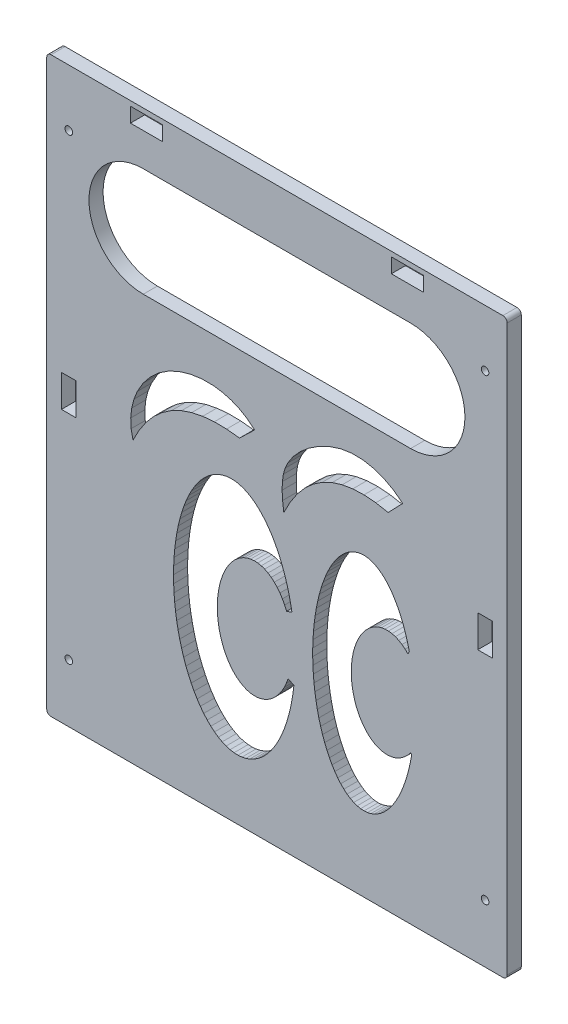
SolidWorks part; units mm, degrees
ref_plane "Front Plane" through (0, 0, 0) normal (0, 0, 1) x (1, 0, 0)
ref_plane "Top Plane" through (0, 0, 0) normal (0, 1, 0) x (1, 0, 0)
ref_plane "Right Plane" through (0, 0, 0) normal (1, 0, 0) x (0, 0, -1)
sketch "Model" plane through (0, 0, 0) normal (0, 0, 1) x (1, 0, 0)
  line L0 (166.4528, 168.5051) -> (162.3208, 171.6508)
  line L1 (162.3208, 171.6508) -> (157.7819, 174.1382)
  line L2 (157.7819, 174.1382) -> (152.9264, 175.8982)
  line L3 (152.9264, 175.8982) -> (147.8445, 176.8622)
  line L4 (147.8445, 176.8622) -> (142.6264, 176.9611)
  line L5 (142.6264, 176.9611) -> (137.3649, 176.1352)
  line L6 (137.3649, 176.1352) -> (132.1849, 174.4433)
  line L7 (132.1849, 174.4433) -> (127.2343, 172.0278)
  line L8 (127.2343, 172.0278) -> (122.6612, 169.0328)
  line L9 (122.6612, 169.0328) -> (118.6141, 165.6027)
  line L10 (118.6141, 165.6027) -> (115.2411, 161.8816)
  line L11 (115.2411, 161.8816) -> (112.6877, 158.0066)
  line L12 (112.6877, 158.0066) -> (111.4758, 155.3153)
  line L13 (111.4758, 155.3153) -> (110.6436, 152.4305)
  line L14 (110.6436, 152.4305) -> (110.1777, 149.2546)
  line L15 (110.1777, 149.2546) -> (110.065, 145.6897)
  line L16 (110.065, 145.6897) -> (110.292, 141.6382)
  line L17 (110.292, 141.6382) -> (110.8456, 137.0023)
  line L18 (110.8456, 137.0023) -> (113.7945, 142.6541)
  line L19 (113.7945, 142.6541) -> (117.0741, 147.6123)
  line L20 (117.0741, 147.6123) -> (120.6843, 151.8768)
  line L21 (120.6843, 151.8768) -> (124.6252, 155.4477)
  line L22 (124.6252, 155.4477) -> (128.8968, 158.3248)
  line L23 (128.8968, 158.3248) -> (133.499, 160.5083)
  line L24 (133.499, 160.5083) -> (138.1411, 161.9316)
  line L25 (138.1411, 161.9316) -> (143.0771, 162.7383)
  line L26 (143.0771, 162.7383) -> (148.3071, 162.9283)
  line L27 (148.3071, 162.9283) -> (153.8311, 162.5017)
  line L28 (153.8311, 162.5017) -> (159.649, 161.4583)
  line L29 (112.8319, 70.6815) -> (112.0081, 68.4661)
  line L30 (112.0081, 68.4661) -> (111.0551, 66.3808)
  line L31 (111.0551, 66.3808) -> (109.9812, 64.4439)
  line L32 (109.9812, 64.4439) -> (108.7959, 62.6723)
  line L33 (108.7959, 62.6723) -> (107.5095, 61.0816)
  line L34 (107.5095, 61.0816) -> (106.1333, 59.6858)
  line L35 (106.1333, 59.6858) -> (104.6795, 58.4971)
  line L36 (104.6795, 58.4971) -> (103.1608, 57.526)
  line L37 (103.1608, 57.526) -> (101.5905, 56.7809)
  line L38 (101.5905, 56.7809) -> (99.9824, 56.2686)
  line L39 (99.9824, 56.2686) -> (98.3507, 55.9933)
  line L40 (98.3507, 55.9933) -> (96.7096, 55.9576)
  line L41 (96.7096, 55.9576) -> (95.0735, 56.1617)
  line L42 (95.0735, 56.1617) -> (93.4569, 56.604)
  line L43 (93.4569, 56.604) -> (91.8739, 57.2804)
  line L44 (91.8739, 57.2804) -> (90.3384, 58.185)
  line L45 (90.3384, 58.185) -> (88.8639, 59.31)
  line L46 (88.8639, 59.31) -> (87.4634, 60.6454)
  line L47 (87.4634, 60.6454) -> (86.1491, 62.1795)
  line L48 (86.1491, 62.1795) -> (84.9325, 63.8988)
  line L49 (84.9325, 63.8988) -> (83.8244, 65.7883)
  line L50 (83.8244, 65.7883) -> (82.8345, 67.8313)
  line L51 (82.8345, 67.8313) -> (81.9715, 70.01)
  line L52 (81.9715, 70.01) -> (81.2429, 72.3051)
  line L53 (81.2429, 72.3051) -> (80.6552, 74.6966)
  line L54 (80.6552, 74.6966) -> (80.2134, 77.1635)
  line L55 (80.2134, 77.1635) -> (79.9216, 79.684)
  line L56 (79.9216, 79.684) -> (79.7822, 82.2361)
  line L57 (79.7822, 82.2361) -> (79.7964, 84.7974)
  line L58 (79.7964, 84.7974) -> (79.9642, 87.3453)
  line L59 (79.9642, 87.3453) -> (80.2841, 89.8575)
  line L60 (80.2841, 89.8575) -> (80.7532, 92.312)
  line L61 (80.7532, 92.312) -> (81.3675, 94.6872)
  line L62 (81.3675, 94.6872) -> (82.1216, 96.9623)
  line L63 (82.1216, 96.9623) -> (83.0087, 99.1172)
  line L64 (83.0087, 99.1172) -> (84.0212, 101.1331)
  line L65 (84.0212, 101.1331) -> (85.1502, 102.9923)
  line L66 (85.1502, 102.9923) -> (86.3857, 104.6783)
  line L67 (86.3857, 104.6783) -> (87.7169, 106.1766)
  line L68 (87.7169, 106.1766) -> (89.1321, 107.4738)
  line L69 (89.1321, 107.4738) -> (90.6189, 108.5586)
  line L70 (90.6189, 108.5586) -> (92.1642, 109.4215)
  line L71 (92.1642, 109.4215) -> (93.7545, 110.0548)
  line L72 (93.7545, 110.0548) -> (95.3758, 110.4532)
  line L73 (95.3758, 110.4532) -> (97.0138, 110.6129)
  line L74 (97.0138, 110.6129) -> (98.6543, 110.5327)
  line L75 (98.6543, 110.5327) -> (100.2827, 110.2132)
  line L76 (100.2827, 110.2132) -> (101.8849, 109.6573)
  line L77 (101.8849, 109.6573) -> (103.4466, 108.8698)
  line L78 (103.4466, 108.8698) -> (104.9543, 107.8577)
  line L79 (104.9543, 107.8577) -> (106.3947, 106.6298)
  line L80 (106.3947, 106.6298) -> (107.7551, 105.1969)
  line L81 (107.7551, 105.1969) -> (109.0236, 103.5715)
  line L82 (109.0236, 103.5715) -> (110.189, 101.768)
  line L83 (110.189, 101.768) -> (111.2412, 99.8023)
  line L84 (111.2412, 99.8023) -> (112.1708, 97.6914)
  line L85 (114.6549, 98.564) -> (113.998, 101.9961)
  line L86 (113.998, 101.9961) -> (113.229, 105.3482)
  line L87 (113.229, 105.3482) -> (112.3512, 108.6062)
  line L88 (112.3512, 108.6062) -> (111.3682, 111.756)
  line L89 (111.3682, 111.756) -> (110.2844, 114.7842)
  line L90 (110.2844, 114.7842) -> (109.1042, 117.6779)
  line L91 (109.1042, 117.6779) -> (107.8329, 120.4248)
  line L92 (107.8329, 120.4248) -> (106.4757, 123.0131)
  line L93 (106.4757, 123.0131) -> (105.0385, 125.4318)
  line L94 (105.0385, 125.4318) -> (103.5274, 127.6705)
  line L95 (103.5274, 127.6705) -> (101.9488, 129.7198)
  line L96 (101.9488, 129.7198) -> (100.3096, 131.5707)
  line L97 (100.3096, 131.5707) -> (98.6167, 133.2155)
  line L98 (98.6167, 133.2155) -> (96.8773, 134.6471)
  line L99 (96.8773, 134.6471) -> (95.0988, 135.8594)
  line L100 (95.0988, 135.8594) -> (93.2889, 136.8473)
  line L101 (93.2889, 136.8473) -> (91.4553, 137.6064)
  line L102 (91.4553, 137.6064) -> (89.6058, 138.1337)
  line L103 (89.6058, 138.1337) -> (87.7483, 138.4267)
  line L104 (87.7483, 138.4267) -> (85.8907, 138.4843)
  line L105 (85.8907, 138.4843) -> (84.041, 138.3063)
  line L106 (84.041, 138.3063) -> (82.207, 137.8933)
  line L107 (82.207, 137.8933) -> (80.3966, 137.2471)
  line L108 (80.3966, 137.2471) -> (78.6175, 136.3706)
  line L109 (78.6175, 136.3706) -> (76.8774, 135.2674)
  line L110 (76.8774, 135.2674) -> (75.1836, 133.9423)
  line L111 (75.1836, 133.9423) -> (73.5433, 132.4009)
  line L112 (73.5433, 132.4009) -> (71.9636, 130.6498)
  line L113 (71.9636, 130.6498) -> (70.4512, 128.6964)
  line L114 (70.4512, 128.6964) -> (69.0126, 126.5492)
  line L115 (69.0126, 126.5492) -> (67.654, 124.2172)
  line L116 (67.654, 124.2172) -> (66.381, 121.7105)
  line L117 (66.381, 121.7105) -> (65.1992, 119.0397)
  line L118 (65.1992, 119.0397) -> (64.1135, 116.2162)
  line L119 (64.1135, 116.2162) -> (63.1287, 113.2522)
  line L120 (63.1287, 113.2522) -> (62.249, 110.1601)
  line L121 (62.249, 110.1601) -> (61.478, 106.9533)
  line L122 (61.478, 106.9533) -> (60.8191, 103.6455)
  line L123 (60.8191, 103.6455) -> (60.2751, 100.2507)
  line L124 (60.2751, 100.2507) -> (59.8483, 96.7834)
  line L125 (59.8483, 96.7834) -> (59.5405, 93.2585)
  line L126 (59.5405, 93.2585) -> (59.3531, 89.691)
  line L127 (59.3531, 89.691) -> (59.2869, 86.0961)
  line L128 (59.2869, 86.0961) -> (59.3421, 82.4892)
  line L129 (59.3421, 82.4892) -> (59.5185, 78.8857)
  line L130 (59.5185, 78.8857) -> (59.8153, 75.3009)
  line L131 (59.8153, 75.3009) -> (60.2313, 71.7502)
  line L132 (60.2313, 71.7502) -> (60.7647, 68.2487)
  line L133 (60.7647, 68.2487) -> (61.4132, 64.8114)
  line L134 (61.4132, 64.8114) -> (62.1741, 61.4529)
  line L135 (62.1741, 61.4529) -> (63.0441, 58.1876)
  line L136 (63.0441, 58.1876) -> (64.0195, 55.0295)
  line L137 (64.0195, 55.0295) -> (65.0962, 51.9919)
  line L138 (65.0962, 51.9919) -> (66.2694, 49.0879)
  line L139 (66.2694, 49.0879) -> (67.5343, 46.3298)
  line L140 (67.5343, 46.3298) -> (68.8854, 43.7296)
  line L141 (68.8854, 43.7296) -> (70.317, 41.2981)
  line L142 (70.317, 41.2981) -> (71.8229, 39.0459)
  line L143 (71.8229, 39.0459) -> (73.3967, 36.9825)
  line L144 (73.3967, 36.9825) -> (75.0317, 35.1168)
  line L145 (75.0317, 35.1168) -> (76.721, 33.4566)
  line L146 (76.721, 33.4566) -> (78.4572, 32.0092)
  line L147 (78.4572, 32.0092) -> (80.233, 30.7807)
  line L148 (80.233, 30.7807) -> (82.0409, 29.7763)
  line L149 (82.0409, 29.7763) -> (83.873, 29.0003)
  line L150 (83.873, 29.0003) -> (85.7217, 28.456)
  line L151 (85.7217, 28.456) -> (87.5789, 28.1458)
  line L152 (87.5789, 28.1458) -> (89.4367, 28.0709)
  line L153 (89.4367, 28.0709) -> (91.2873, 28.2317)
  line L154 (91.2873, 28.2317) -> (93.1227, 28.6276)
  line L155 (93.1227, 28.6276) -> (94.9351, 29.2567)
  line L156 (94.9351, 29.2567) -> (96.7167, 30.1165)
  line L157 (96.7167, 30.1165) -> (98.4599, 31.2033)
  line L158 (98.4599, 31.2033) -> (100.1574, 32.5124)
  line L159 (100.1574, 32.5124) -> (101.8018, 34.0382)
  line L160 (101.8018, 34.0382) -> (103.3862, 35.7742)
  line L161 (103.3862, 35.7742) -> (104.9037, 37.713)
  line L162 (104.9037, 37.713) -> (106.3479, 39.8464)
  line L163 (106.3479, 39.8464) -> (107.7126, 42.1651)
  line L164 (107.7126, 42.1651) -> (108.9921, 44.6594)
  line L165 (108.9921, 44.6594) -> (110.1807, 47.3186)
  line L166 (110.1807, 47.3186) -> (111.2735, 50.1313)
  line L167 (111.2735, 50.1313) -> (112.2659, 53.0855)
  line L168 (112.2659, 53.0855) -> (113.1535, 56.1686)
  line L169 (113.1535, 56.1686) -> (113.9325, 59.3675)
  line L170 (113.9325, 59.3675) -> (114.5997, 62.6684)
  line L171 (114.5997, 62.6684) -> (115.1522, 66.0574)
  line L172 (115.1522, 66.0574) -> (115.5876, 69.5198)
  line L173 (97.1998, 163.6453) -> (93.8138, 166.4213)
  line L174 (93.8138, 166.4213) -> (90.1204, 168.6313)
  line L175 (90.1204, 168.6313) -> (86.1819, 170.2877)
  line L176 (86.1819, 170.2877) -> (82.0607, 171.4026)
  line L177 (82.0607, 171.4026) -> (77.8193, 171.9883)
  line L178 (77.8193, 171.9883) -> (72.4434, 171.9946)
  line L179 (72.4434, 171.9946) -> (67.099, 171.2169)
  line L180 (67.099, 171.2169) -> (61.908, 169.679)
  line L181 (61.908, 169.679) -> (56.9923, 167.4046)
  line L182 (56.9923, 167.4046) -> (52.4736, 164.4177)
  line L183 (52.4736, 164.4177) -> (48.4677, 160.7608)
  line L184 (48.4677, 160.7608) -> (45.0691, 156.5389)
  line L185 (45.0691, 156.5389) -> (42.3678, 151.87)
  line L186 (42.3678, 151.87) -> (40.7695, 147.8923)
  line L187 (40.7695, 147.8923) -> (39.7213, 143.7644)
  line L188 (39.7213, 143.7644) -> (39.2695, 139.5469)
  line L189 (39.2695, 139.5469) -> (39.4602, 135.3)
  line L190 (39.4602, 135.3) -> (40.3395, 131.0842)
  line L191 (40.3395, 131.0842) -> (43.206, 136.5382)
  line L192 (43.206, 136.5382) -> (46.4396, 141.3642)
  line L193 (46.4396, 141.3642) -> (50.0401, 145.5623)
  line L194 (50.0401, 145.5623) -> (54.0078, 149.1325)
  line L195 (54.0078, 149.1325) -> (58.3424, 152.0747)
  line L196 (58.3424, 152.0747) -> (63.0441, 154.389)
  line L197 (63.0441, 154.389) -> (67.8133, 155.9959)
  line L198 (67.8133, 155.9959) -> (72.9088, 157.0446)
  line L199 (72.9088, 157.0446) -> (78.3306, 157.5351)
  line L200 (78.3306, 157.5351) -> (84.0787, 157.4674)
  line L201 (84.0787, 157.4674) -> (90.153, 156.8415)
  line L202 (169.556, 110.1014) -> (168.7807, 113.16)
  line L203 (168.7807, 113.16) -> (167.912, 116.0984)
  line L204 (167.912, 116.0984) -> (166.9538, 118.9033)
  line L205 (166.9538, 118.9033) -> (165.9106, 121.5619)
  line L206 (165.9106, 121.5619) -> (164.7871, 124.0622)
  line L207 (164.7871, 124.0622) -> (163.5884, 126.3927)
  line L208 (163.5884, 126.3927) -> (162.32, 128.5429)
  line L209 (162.32, 128.5429) -> (160.9875, 130.5031)
  line L210 (160.9875, 130.5031) -> (159.5971, 132.2642)
  line L211 (159.5971, 132.2642) -> (158.1551, 133.8183)
  line L212 (158.1551, 133.8183) -> (156.668, 135.1584)
  line L213 (156.668, 135.1584) -> (155.1427, 136.2783)
  line L214 (155.1427, 136.2783) -> (153.5859, 137.1729)
  line L215 (153.5859, 137.1729) -> (152.0049, 137.8382)
  line L216 (152.0049, 137.8382) -> (150.4068, 138.2712)
  line L217 (150.4068, 138.2712) -> (148.7989, 138.4698)
  line L218 (148.7989, 138.4698) -> (147.1884, 138.4332)
  line L219 (147.1884, 138.4332) -> (145.5827, 138.1616)
  line L220 (145.5827, 138.1616) -> (143.9891, 137.6561)
  line L221 (143.9891, 137.6561) -> (142.4149, 136.9191)
  line L222 (142.4149, 136.9191) -> (140.8672, 135.954)
  line L223 (140.8672, 135.954) -> (139.353, 134.765)
  line L224 (139.353, 134.765) -> (137.8792, 133.3577)
  line L225 (137.8792, 133.3577) -> (136.4526, 131.7384)
  line L226 (136.4526, 131.7384) -> (135.0795, 129.9145)
  line L227 (135.0795, 129.9145) -> (133.7663, 127.8942)
  line L228 (133.7663, 127.8942) -> (132.5189, 125.6869)
  line L229 (132.5189, 125.6869) -> (131.343, 123.3024)
  line L230 (131.343, 123.3024) -> (130.244, 120.7516)
  line L231 (130.244, 120.7516) -> (129.2268, 118.0462)
  line L232 (129.2268, 118.0462) -> (128.296, 115.1984)
  line L233 (128.296, 115.1984) -> (127.4559, 112.2212)
  line L234 (127.4559, 112.2212) -> (126.7103, 109.128)
  line L235 (126.7103, 109.128) -> (126.0627, 105.9331)
  line L236 (126.0627, 105.9331) -> (125.5158, 102.6509)
  line L237 (125.5158, 102.6509) -> (125.0723, 99.2962)
  line L238 (125.0723, 99.2962) -> (124.7341, 95.8845)
  line L239 (124.7341, 95.8845) -> (124.5028, 92.4311)
  line L240 (124.5028, 92.4311) -> (124.3795, 88.9518)
  line L241 (124.3795, 88.9518) -> (124.3646, 85.4624)
  line L242 (124.3646, 85.4624) -> (124.4583, 81.9788)
  line L243 (124.4583, 81.9788) -> (124.6602, 78.5167)
  line L244 (124.6602, 78.5167) -> (124.9692, 75.0921)
  line L245 (124.9692, 75.0921) -> (125.3841, 71.7203)
  line L246 (125.3841, 71.7203) -> (125.9028, 68.4167)
  line L247 (125.9028, 68.4167) -> (126.5232, 65.1964)
  line L248 (126.5232, 65.1964) -> (127.2423, 62.074)
  line L249 (127.2423, 62.074) -> (128.0569, 59.0637)
  line L250 (128.0569, 59.0637) -> (128.9632, 56.1792)
  line L251 (128.9632, 56.1792) -> (129.9572, 53.4335)
  line L252 (129.9572, 53.4335) -> (131.0344, 50.8392)
  line L253 (131.0344, 50.8392) -> (132.1898, 48.4081)
  line L254 (132.1898, 48.4081) -> (133.4181, 46.1512)
  line L255 (133.4181, 46.1512) -> (134.7139, 44.0788)
  line L256 (134.7139, 44.0788) -> (136.0712, 42.2003)
  line L257 (136.0712, 42.2003) -> (137.4838, 40.5242)
  line L258 (137.4838, 40.5242) -> (138.9453, 39.0582)
  line L259 (138.9453, 39.0582) -> (140.4491, 37.8089)
  line L260 (140.4491, 37.8089) -> (141.9884, 36.7821)
  line L261 (141.9884, 36.7821) -> (143.5561, 35.9823)
  line L262 (143.5561, 35.9823) -> (145.145, 35.4132)
  line L263 (145.145, 35.4132) -> (146.7481, 35.0773)
  line L264 (146.7481, 35.0773) -> (148.358, 34.9764)
  line L265 (148.358, 34.9764) -> (149.9674, 35.1107)
  line L266 (149.9674, 35.1107) -> (151.5689, 35.4796)
  line L267 (151.5689, 35.4796) -> (153.1553, 36.0816)
  line L268 (153.1553, 36.0816) -> (154.7194, 36.9138)
  line L269 (154.7194, 36.9138) -> (156.2541, 37.9725)
  line L270 (156.2541, 37.9725) -> (157.7523, 39.2529)
  line L271 (157.7523, 39.2529) -> (159.2073, 40.7491)
  line L272 (159.2073, 40.7491) -> (160.6125, 42.4543)
  line L273 (160.6125, 42.4543) -> (161.9614, 44.3608)
  line L274 (161.9614, 44.3608) -> (163.248, 46.46)
  line L275 (163.248, 46.46) -> (164.4663, 48.7422)
  line L276 (164.4663, 48.7422) -> (165.6109, 51.1971)
  line L277 (165.6109, 51.1971) -> (166.6766, 53.8135)
  line L278 (166.6766, 53.8135) -> (167.6584, 56.5796)
  line L279 (167.6584, 56.5796) -> (168.552, 59.4828)
  line L280 (168.552, 59.4828) -> (169.3533, 62.5098)
  line L281 (169.3533, 62.5098) -> (170.0586, 65.647)
  line L282 (170.0586, 65.647) -> (170.6647, 68.88)
  line L283 (170.1423, 69.3554) -> (168.8654, 67.8281)
  line L284 (168.8654, 67.8281) -> (167.4959, 66.4955)
  line L285 (167.4959, 66.4955) -> (166.0469, 65.3703)
  line L286 (166.0469, 65.3703) -> (164.5321, 64.4632)
  line L287 (164.5321, 64.4632) -> (162.9659, 63.7828)
  line L288 (162.9659, 63.7828) -> (161.3632, 63.3355)
  line L289 (161.3632, 63.3355) -> (159.7393, 63.1257)
  line L290 (159.7393, 63.1257) -> (158.1095, 63.1553)
  line L291 (158.1095, 63.1553) -> (156.4894, 63.424)
  line L292 (156.4894, 63.424) -> (154.8944, 63.9293)
  line L293 (154.8944, 63.9293) -> (153.3395, 64.6664)
  line L294 (153.3395, 64.6664) -> (151.8397, 65.6283)
  line L295 (151.8397, 65.6283) -> (150.409, 66.8058)
  line L296 (150.409, 66.8058) -> (149.0612, 68.1877)
  line L297 (149.0612, 68.1877) -> (147.809, 69.761)
  line L298 (147.809, 69.761) -> (146.6643, 71.5106)
  line L299 (146.6643, 71.5106) -> (145.6381, 73.42)
  line L300 (145.6381, 73.42) -> (144.74, 75.4709)
  line L301 (144.74, 75.4709) -> (143.9786, 77.644)
  line L302 (143.9786, 77.644) -> (143.3611, 79.9185)
  line L303 (143.3611, 79.9185) -> (142.8934, 82.2729)
  line L304 (142.8934, 82.2729) -> (142.5799, 84.6848)
  line L305 (142.5799, 84.6848) -> (142.4237, 87.1312)
  line L306 (142.4237, 87.1312) -> (142.4261, 89.5889)
  line L307 (142.4261, 89.5889) -> (142.5873, 92.0347)
  line L308 (142.5873, 92.0347) -> (142.9055, 94.4451)
  line L309 (142.9055, 94.4451) -> (143.3779, 96.7973)
  line L310 (143.3779, 96.7973) -> (143.9999, 99.0691)
  line L311 (143.9999, 99.0691) -> (144.7657, 101.2387)
  line L312 (144.7657, 101.2387) -> (145.6679, 103.2856)
  line L313 (145.6679, 103.2856) -> (146.6979, 105.1903)
  line L314 (146.6979, 105.1903) -> (147.8461, 106.9347)
  line L315 (147.8461, 106.9347) -> (149.1014, 108.5022)
  line L316 (149.1014, 108.5022) -> (150.452, 109.8781)
  line L317 (150.452, 109.8781) -> (151.885, 111.0491)
  line L318 (151.885, 111.0491) -> (153.3868, 112.0041)
  line L319 (153.3868, 112.0041) -> (154.9431, 112.7341)
  line L320 (154.9431, 112.7341) -> (156.5391, 113.2322)
  line L321 (156.5391, 113.2322) -> (158.1598, 113.4936)
  line L322 (158.1598, 113.4936) -> (159.7896, 113.5158)
  line L323 (159.7896, 113.5158) -> (161.4131, 113.2986)
  line L324 (161.4131, 113.2986) -> (163.0148, 112.8441)
  line L325 (163.0148, 112.8441) -> (164.5796, 112.1566)
  line L326 (164.5796, 112.1566) -> (166.0926, 111.2426)
  line L327 (166.0926, 111.2426) -> (167.5394, 110.1108)
  line L328 (167.5394, 110.1108) -> (168.9062, 108.772)
  line L329 (159.649, 161.4583) -> (166.4528, 168.5051)
  line L330 (115.5876, 69.5198) -> (112.8319, 70.6815)
  line L331 (112.1708, 97.6914) -> (114.6549, 98.564)
  line L332 (54.14, 258.87) -> (54.14, 265.73)
  line L333 (39.14, 265.73) -> (54.14, 265.73)
  line L334 (39.14, 258.87) -> (39.14, 265.73)
  line L335 (54.14, 258.87) -> (39.14, 258.87)
  line L336 (161.14, 258.87) -> (161.14, 265.73)
  line L337 (161.14, 258.87) -> (176.14, 258.87)
  line L338 (176.14, 258.87) -> (176.14, 265.73)
  line L339 (176.14, 265.73) -> (161.14, 265.73)
  line L340 (6.88, 141.82) -> (13.74, 141.82)
  line L341 (6.88, 141.82) -> (6.88, 126.82)
  line L342 (6.88, 126.82) -> (13.74, 126.82)
  line L343 (13.74, 141.82) -> (13.74, 126.82)
  line L344 (0, 266) -> (0, 2)
  line L345 (213.28, 268) -> (2, 268)
  line L346 (215.28, 2) -> (215.28, 266)
  line L347 (2, 0) -> (213.28, 0)
  line L348 (201.54, 141.82) -> (208.4, 141.82)
  line L349 (201.54, 141.82) -> (201.54, 126.82)
  line L350 (201.54, 126.82) -> (208.4, 126.82)
  line L351 (208.4, 141.82) -> (208.4, 126.82)
  line L352 (90.153, 156.8415) -> (97.1998, 163.6453)
  line L353 (168.9062, 108.772) -> (169.556, 110.1014)
  line L354 (170.6647, 68.88) -> (170.1423, 69.3554)
  line L355 (45.14, 192.6) -> (170.14, 192.6)
  line L356 (170.14, 243.4) -> (45.14, 243.4)
  circle A0 centre (10.31, 241.465) radius 1.775
  circle A1 centre (204.97, 241.465) radius 1.775
  circle A2 centre (10.31, 27.175) radius 1.775
  circle A3 centre (204.97, 27.175) radius 1.775
  arc A4 (0, 2) -> (2, 0) centre (2, 2) ccw
  arc A5 (2, 268) -> (0, 266) centre (2, 266) ccw
  arc A6 (215.28, 266) -> (213.28, 268) centre (213.28, 266) ccw
  arc A7 (213.28, 0) -> (215.28, 2) centre (213.28, 2) ccw
  arc A8 (45.14, 243.4) -> (45.14, 192.6) centre (45.14, 218) ccw
  arc A9 (170.14, 192.6) -> (170.14, 243.4) centre (170.14, 218) ccw
extrude "Boss-Extrude1" add sketch "Model" along normal blind 6.6
